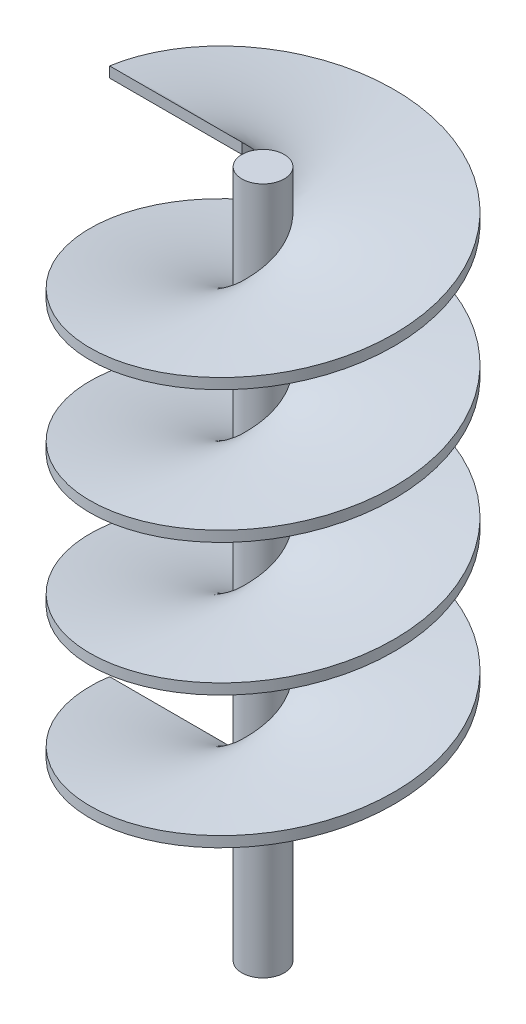
SolidWorks part; units mm, degrees
ref_plane "Front Plane" through (0, 0, 0) normal (0, 0, 1) x (1, 0, 0)
ref_plane "Top Plane" through (0, 0, 0) normal (0, 1, 0) x (1, 0, 0)
ref_plane "Right Plane" through (0, 0, 0) normal (1, 0, 0) x (0, 0, -1)
sketch "Sketch1" plane through (0, 0, 0) normal (0, 1, 0) x (1, 0, 0)
  circle A0 centre (0, 0) radius 4
extrude "Boss-Extrude1" add sketch "Sketch1" along normal blind 130
sketch "Sketch5" plane through (0, 130, 0) normal (0, 1, 0) x (1, 0, 0)
  circle A0 centre (0, 0) radius 4 construction
  circle A1 centre (0, 0) radius 4
curve "Helix/Spiral1" pitch 25 height 100 turns 4
ref_plane "Plane1" through (-4, 130, 0) normal (0, 0, 1) x (1, 0, 0)
sketch "Sketch6" plane through (-4, 130, 0) normal (0, 0, 1) x (1, 0, 0)
  line L1 (0, 0) -> (-25, 0)
  line L2 (0, 0) -> (0, 2)
  line L3 (0, 2) -> (-25, 2)
  line L4 (-25, 0) -> (-25, 2)
  dimension "D1" = 2
  dimension "D2" = 25
sweep "Sweep1" add profiles "Sketch6" path "Helix/Spiral1"
